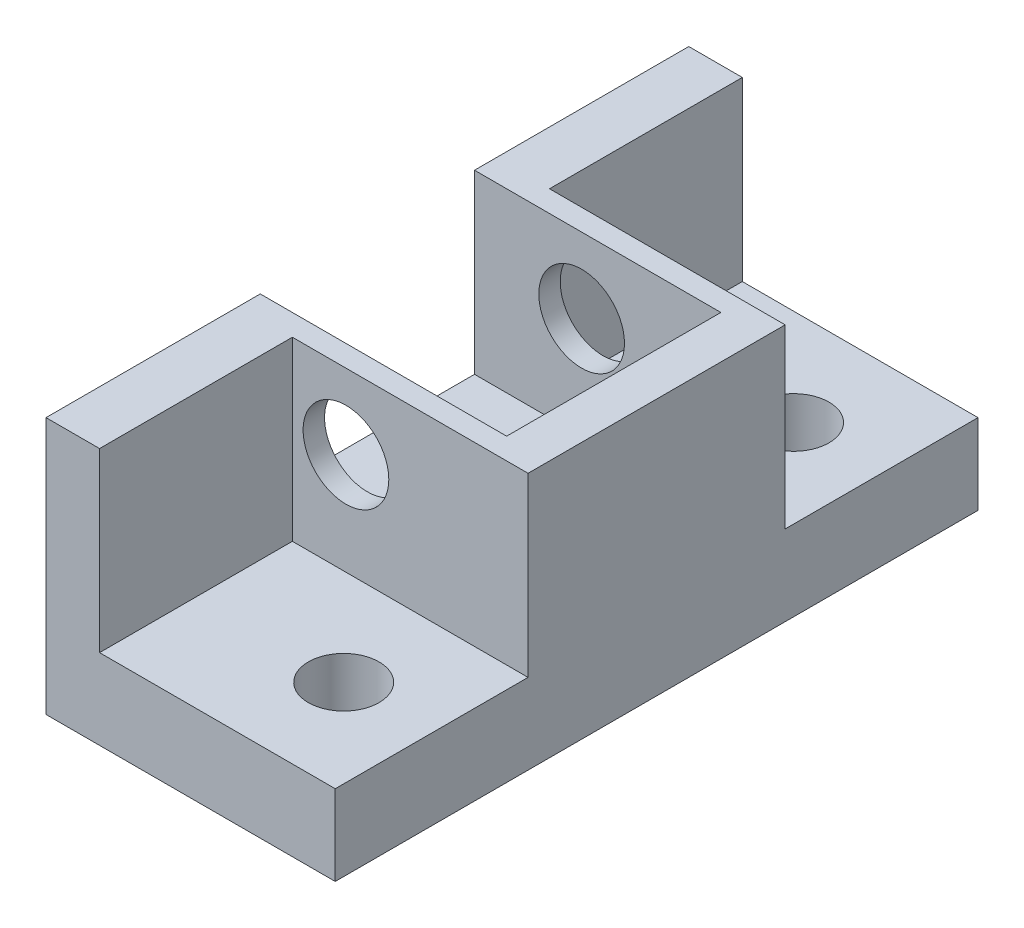
SolidWorks part; units mm, degrees
ref_plane "Front Plane" through (0, 0, 0) normal (0, 0, 1) x (1, 0, 0)
ref_plane "Top Plane" through (0, 0, 0) normal (0, 1, 0) x (1, 0, 0)
ref_plane "Right Plane" through (0, 0, 0) normal (1, 0, 0) x (0, 0, -1)
sketch "Sketch2" plane through (0, 0, 0) normal (0, 1, 0) x (1, 0, 0)
  line L1 (13.5, -30) -> (-13.5, -30)
  line L2 (13.5, -30) -> (13.5, 30)
  line L3 (13.5, 30) -> (-13.5, 30)
  line L4 (-13.5, -30) -> (-13.5, 30)
  line L5 (13.5, -30) -> (-13.5, 30) construction
  line L6 (13.5, 30) -> (-13.5, -30) construction
  point P0 (0, 0)
  dimension "D1" = 60
  dimension "D2" = 27
extrude "Boss-Extrude1" add sketch "Sketch2" along normal blind 7.5
sketch "Sketch3" plane through (0, 7.5, 0) normal (0, 1, 0) x (1, 0, 0)
  line L0 (-13.5, -30) -> (-8.5, -30)
  line L1 (-13.5, -30) -> (13.5, -30) construction
  line L2 (-8.5, -30) -> (-8.5, -12)
  line L4 (-13.5, 30) -> (-13.5, 10)
  line L7 (-13.5, 30) -> (-13.5, -30) construction
  line L10 (-13.5, 10) -> (9.5, 10)
  line L12 (13.5, -12) -> (13.5, 12)
  line L13 (13.5, 12) -> (-8.5, 12)
  line L14 (-8.5, 12) -> (-8.5, 30)
  line L15 (13.5, 30) -> (-13.5, 30) construction
  line L16 (-8.5, 30) -> (-13.5, 30)
  line L18 (13.5, -12) -> (-8.5, -12)
  line L19 (9.5, 10) -> (9.5, -10)
  line L20 (9.5, -10) -> (-13.5, -10)
  line L21 (-13.5, -10) -> (-13.5, -30)
  line L23 (13.5, -30) -> (13.5, 30) construction
  point P5 (13.5, -12)
  point P18 (13.5, 0)
  point P24 (0, 0)
  point P25 (9.5, 0)
  dimension "D1" = 20
  dimension "D2" = 24
  dimension "D3" = 4
  dimension "D4" = 5
extrude "Boss-Extrude2" add sketch "Sketch3" along normal blind 16.5
sketch "Sketch4" plane through (0, 0, 12) normal (0, 0, 1) x (1, 0, 0)
  line L0 (-8.5, 24) -> (13.5, 24) construction
  line L1 (-8.5, 24) -> (-8.5, 7.5) construction
  circle A0 centre (-3.5, 17) radius 4
  dimension "D1" = 8
  dimension "D2" = 7
  dimension "D3" = 5
extrude "Cut-Extrude1" cut sketch "Sketch4" against normal through all
sketch "Sketch5" plane through (0, 7.5, 0) normal (0, 1, 0) x (1, 0, 0)
  line L0 (0, 0) -> (26.8223, 0) construction
  circle A0 centre (5.2875, -21) radius 3.3
  circle A1 centre (5.2875, 21) radius 3.3
  dimension "D1" = 6.6
extrude "Cut-Extrude2" cut sketch "Sketch5" against normal through all
